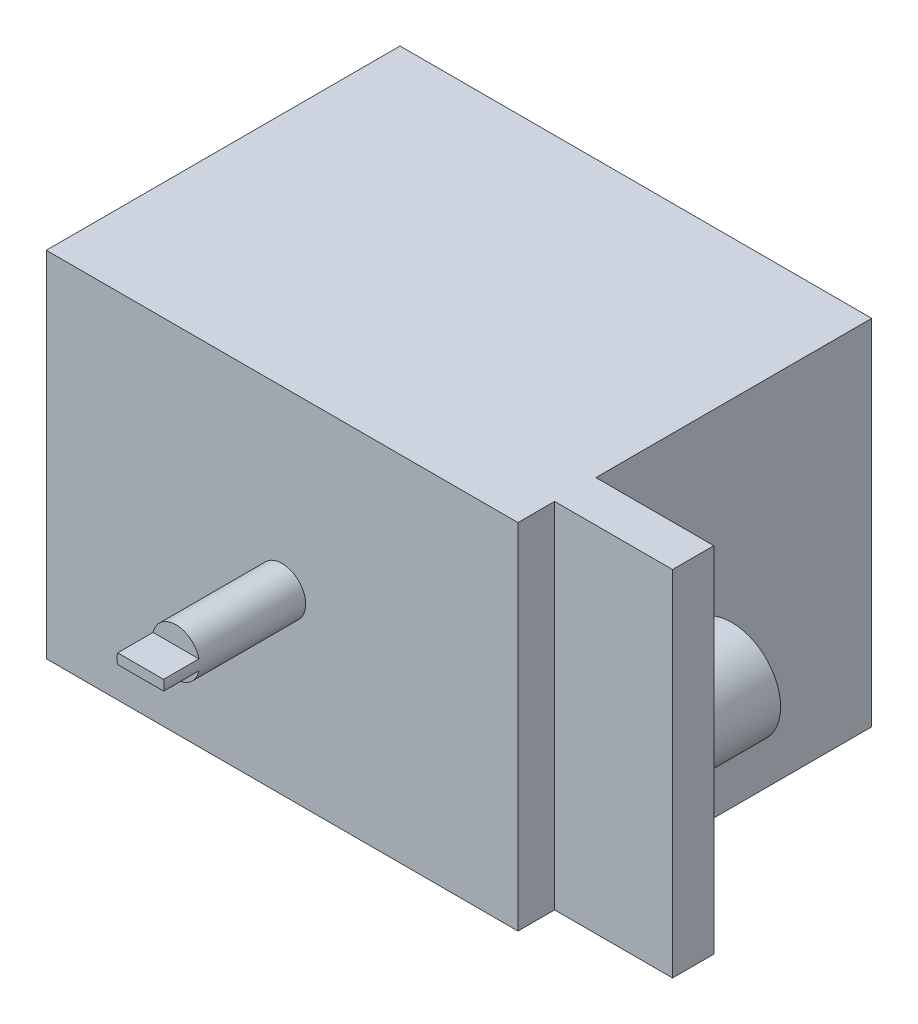
SolidWorks part; units mm, degrees
ref_plane "Front Plane" through (0, 0, 0) normal (0, 0, 1) x (1, 0, 0)
ref_plane "Top Plane" through (0, 0, 0) normal (0, 1, 0) x (1, 0, 0)
ref_plane "Right Plane" through (0, 0, 0) normal (1, 0, 0) x (0, 0, -1)
sketch "Sketch1" plane through (0, 0, 0) normal (0, 0, 1) x (1, 0, 0)
  line L1 (-100, -75) -> (100, -75)
  line L2 (-100, -75) -> (-100, 75)
  line L3 (-100, 75) -> (100, 75)
  line L4 (100, -75) -> (100, 75)
  line L5 (-100, -75) -> (100, 75) construction
  line L6 (-100, 75) -> (100, -75) construction
  point P0 (0, 0)
  dimension "D1" = 200
  dimension "D2" = 150
extrude "Boss-Extrude1" add sketch "Sketch1" along normal blind 150
sketch "Sketch2" plane through (0, 0, 0) normal (0, 0, -1) x (-1, 0, 0)
  circle A0 centre (80.0182, 54.1091) radius 14.8342
extrude "Cut-Extrude1" cut sketch "Sketch2" against normal blind 5
pattern_linear "LPattern1" count 3 spacing 50 along (0, -1, 0) of "Cut-Extrude1"
sketch "Sketch3" plane through (100, 0, 0) normal (1, 0, 0) x (0, 0, -1)
  line L0 (-150, 75) -> (0, 75) construction
  line L1 (-134.4604, 75) -> (-116.9668, 75)
  line L2 (-134.4604, 75) -> (-134.4604, -75)
  line L3 (-134.4604, -75) -> (-116.9668, -75)
  line L4 (-116.9668, 75) -> (-116.9668, -75)
  line L5 (-150, -75) -> (0, -75) construction
extrude "Boss-Extrude2" add sketch "Sketch3" along normal blind 50
sketch "Sketch4" plane through (0, 0, 116.9668) normal (0, 0, -1) x (-1, 0, 0)
  circle A0 centre (-127.6681, 0) radius 20.6577
extrude "Boss-Extrude3" add sketch "Sketch4" along normal blind 30
sketch "Sketch5" plane through (0, 0, 150) normal (0, 0, 1) x (1, 0, 0)
  circle A0 centre (0, 0) radius 10
  dimension "D1" = 20
extrude "Boss-Extrude4" add sketch "Sketch5" along normal blind 60
sketch "Sketch6" plane through (0, 0, 210) normal (0, 0, 1) x (1, 0, 0)
  line L1 (-9.7301, 2.3077) -> (10.1975, 2.3077)
  line L2 (-9.7301, 2.3077) -> (-9.7301, 10.7274)
  line L3 (-9.7301, 10.7274) -> (10.1975, 10.7274)
  line L4 (10.1975, 2.3077) -> (10.1975, 10.7274)
  line L5 (9.7994, -1.9931) -> (-11.5768, -1.9931)
  line L6 (9.7994, -1.9931) -> (9.7994, -10)
  line L7 (9.7994, -10) -> (-11.5768, -10)
  line L8 (-11.5768, -1.9931) -> (-11.5768, -10)
  circle A0 centre (0, 0) radius 10 construction
  circle A1 centre (0, 0) radius 10 construction
extrude "Cut-Extrude2" cut sketch "Sketch6" against normal blind 15
